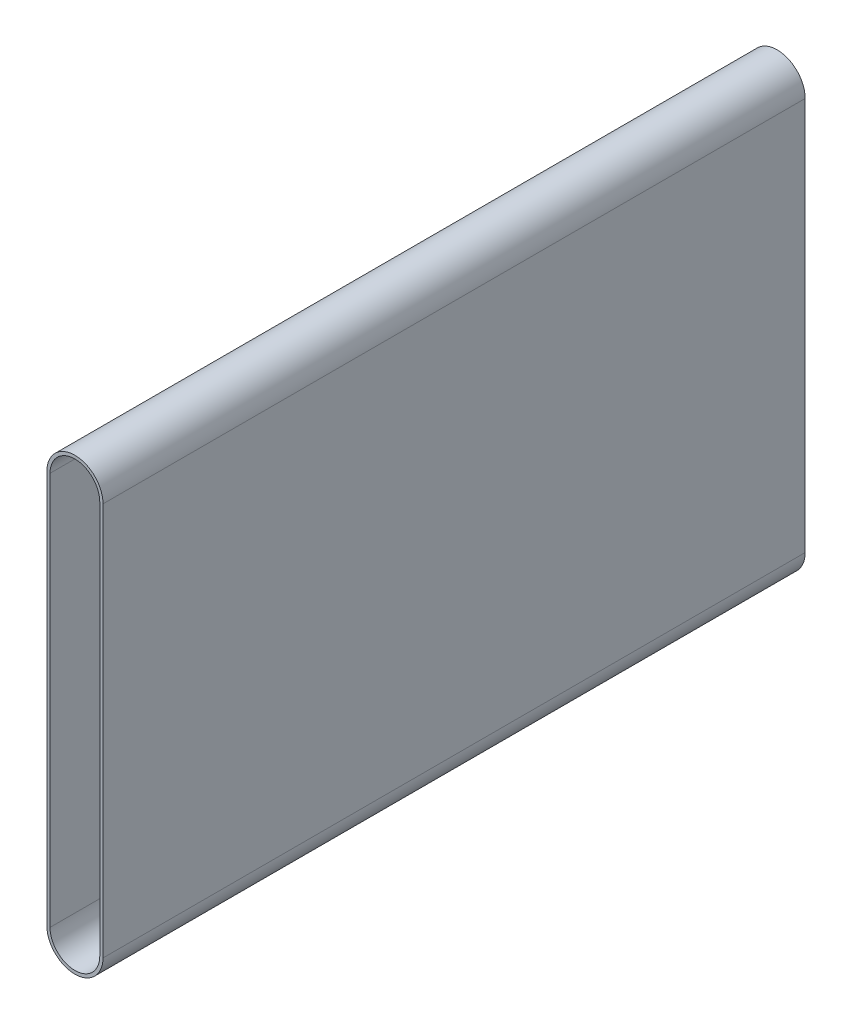
SolidWorks part; units mm, degrees
ref_plane "Plan de face" through (0, 0, 0) normal (0, 0, 1) x (1, 0, 0)
ref_plane "Plan de dessus" through (0, 0, 0) normal (0, 1, 0) x (1, 0, 0)
ref_plane "Plan de droite" through (0, 0, 0) normal (1, 0, 0) x (0, 0, -1)
sketch "Esquisse1" plane through (0, 0, 0) normal (0, 0, 1) x (1, 0, 0)
  line L0 (0, 0) -> (0, 140) construction
  line L1 (-10, 0) -> (-10, 140)
  line L2 (10, 0) -> (10, 140)
  arc A0 (-10, 0) -> (10, 0) centre (0, 0) ccw
  arc A1 (10, 140) -> (-10, 140) centre (0, 140) ccw
  point P3 (0, 70)
extrude "Boss.-Extru.1" add sketch "Esquisse1" along normal blind 250
sketch "Esquisse2" plane through (0, 0, 250) normal (0, 0, 1) x (1, 0, 0)
  line L0 (0, 140) -> (0, 0) construction
  line L1 (8.8569, 140) -> (8.8569, 0)
  line L2 (-8.8569, 140) -> (-8.8569, 0)
  arc A0 (8.8569, 140) -> (-8.8569, 140) centre (0, 140) ccw
  arc A1 (-8.8569, 0) -> (8.8569, 0) centre (0, 0) ccw
  point P4 (0, 70)
extrude "Enlèv. mat.-Extru.1" cut sketch "Esquisse2" against normal blind 250
